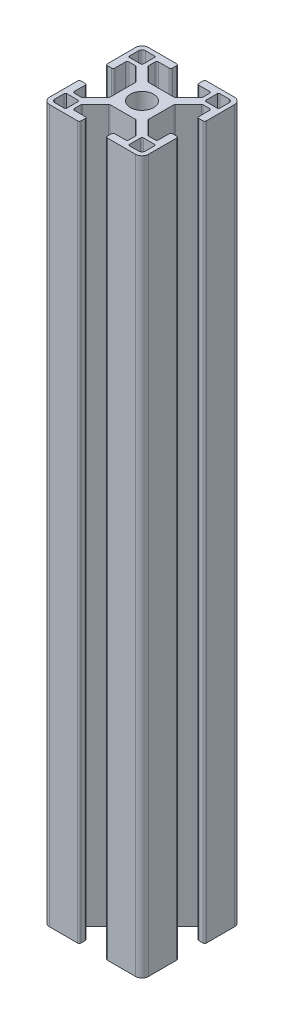
SolidWorks part; units mm, degrees
ref_plane "Front Plane" through (0, 0, 0) normal (0, 0, 1) x (1, 0, 0)
ref_plane "Top Plane" through (0, 0, 0) normal (0, 1, 0) x (1, 0, 0)
ref_plane "Right Plane" through (0, 0, 0) normal (1, 0, 0) x (0, 0, -1)
sketch "Sketch1" plane through (0, 0, 0) normal (0, 1, 0) x (1, 0, 0)
  line L0 (3.9799, -2.4733) -> (3.1981, -1.4942) construction
  line L1 (1.4942, -3.1981) -> (2.4733, -3.9799) construction
  line L2 (-2.4733, -3.9799) -> (-1.4942, -3.1981) construction
  line L3 (-3.1981, -1.4942) -> (-3.9799, -2.4733) construction
  line L4 (-3.9799, 2.4733) -> (-3.1981, 1.4942) construction
  line L5 (-1.4942, 3.1981) -> (-2.4733, 3.9799) construction
  line L6 (2.4733, 3.9799) -> (1.4942, 3.1981) construction
  line L7 (3.1981, 1.4942) -> (3.9799, 2.4733) construction
  line L8 (-12.6999, -13.6999) -> (-9.881, -13.6999)
  line L9 (-13.6999, -9.881) -> (-13.6999, -12.6999)
  line L10 (-9.88, -9.5) -> (-13.3189, -9.5)
  line L11 (-9.5, -13.3189) -> (-9.5, -9.88)
  line L12 (13.6999, -12.6999) -> (13.6999, -9.881)
  line L13 (9.881, -13.6999) -> (12.6999, -13.6999)
  line L14 (9.5, -9.88) -> (9.5, -13.3189)
  line L15 (13.3189, -9.5) -> (9.88, -9.5)
  line L16 (9.88, 9.5) -> (13.3189, 9.5)
  line L17 (9.5, 13.3189) -> (9.5, 9.88)
  line L18 (12.6999, 13.6999) -> (9.881, 13.6999)
  line L19 (13.6999, 9.881) -> (13.6999, 12.6999)
  line L20 (-13.6999, 12.6999) -> (-13.6999, 9.881)
  line L21 (-9.881, 13.6999) -> (-12.6999, 13.6999)
  line L22 (-9.5, 9.88) -> (-9.5, 13.3189)
  line L23 (-13.3189, 9.5) -> (-9.88, 9.5)
  line L24 (14.4999, -4) -> (13.2425, -4)
  line L25 (12.7425, -4.5) -> (12.7425, -7.7325)
  line L26 (12.2428, -8.25) -> (10.2602, -8.25)
  line L27 (9.9066, -8.1035) -> (5.9811, -4.178)
  line L28 (5.8347, -3.8245) -> (5.8347, -1.0125)
  line L29 (5.8347, -1.0125) -> (5.3247, -0.0625) construction
  line L30 (5.3247, -0.0625) -> (5.8347, 0.8875) construction
  line L31 (5.8347, 0.8875) -> (5.8347, 3.8245)
  line L32 (5.9811, 4.178) -> (9.9066, 8.1035)
  line L33 (10.2602, 8.25) -> (12.2428, 8.25)
  line L34 (12.7425, 7.7325) -> (12.7425, 4.5)
  line L35 (13.2425, 4) -> (14.4999, 4)
  line L36 (14.9999, 4.5) -> (14.9999, 12.9999)
  line L37 (12.9999, 14.9999) -> (4.5, 14.9999)
  line L38 (4, 14.4999) -> (4, 13.2425)
  line L39 (4.5, 12.7425) -> (7.7325, 12.7425)
  line L40 (8.25, 12.2428) -> (8.25, 10.2602)
  line L41 (8.1035, 9.9066) -> (4.178, 5.9811)
  line L42 (3.8245, 5.8347) -> (0.95, 5.8347)
  line L43 (0.95, 5.8347) -> (0, 5.3247) construction
  line L44 (0, 5.3247) -> (-0.95, 5.8347) construction
  line L45 (-0.95, 5.8347) -> (-3.8245, 5.8347)
  line L46 (-4.178, 5.9811) -> (-8.1035, 9.9066)
  line L47 (-8.25, 10.2602) -> (-8.25, 12.2428)
  line L48 (-7.7325, 12.7425) -> (-4.5, 12.7425)
  line L49 (-4, 13.2425) -> (-4, 14.4999)
  line L50 (-4.5, 14.9999) -> (-12.9999, 14.9999)
  line L51 (-14.9999, 12.9999) -> (-14.9999, 4.5)
  line L52 (-14.4999, 4) -> (-13.2425, 4)
  line L53 (-12.7425, 4.5) -> (-12.7425, 7.7325)
  line L54 (-12.2428, 8.25) -> (-10.2602, 8.25)
  line L55 (-9.9066, 8.1035) -> (-5.9811, 4.178)
  line L56 (-5.8347, 3.8245) -> (-5.8347, 0.8875)
  line L57 (-5.8347, 0.8875) -> (-5.3247, -0.0625) construction
  line L58 (-5.3247, -0.0625) -> (-5.8347, -1.0125) construction
  line L59 (-5.8347, -1.0125) -> (-5.8347, -3.8245)
  line L60 (-5.9811, -4.178) -> (-9.9066, -8.1035)
  line L61 (-10.2602, -8.25) -> (-12.2428, -8.25)
  line L62 (-12.7425, -7.7325) -> (-12.7425, -4.5)
  line L63 (-13.2425, -4) -> (-14.4999, -4)
  line L64 (-14.9999, -4.5) -> (-14.9999, -12.9999)
  line L65 (-12.9999, -14.9999) -> (-4.5, -14.9999)
  line L66 (-4, -14.4999) -> (-4, -13.2425)
  line L67 (-4.5, -12.7425) -> (-7.7325, -12.7425)
  line L68 (-8.25, -12.2428) -> (-8.25, -10.2602)
  line L69 (-8.1035, -9.9066) -> (-4.178, -5.9811)
  line L70 (-3.8245, -5.8347) -> (-0.95, -5.8347)
  line L71 (-0.95, -5.8347) -> (0, -5.3247) construction
  line L72 (0, -5.3247) -> (0.95, -5.8347) construction
  line L73 (0.95, -5.8347) -> (3.8245, -5.8347)
  line L74 (4.178, -5.9811) -> (8.1035, -9.9066)
  line L75 (8.25, -10.2602) -> (8.25, -12.2428)
  line L76 (7.7325, -12.7425) -> (4.5, -12.7425)
  line L77 (4, -13.2425) -> (4, -14.4999)
  line L78 (4.5, -14.9999) -> (12.9999, -14.9999)
  line L79 (14.9999, -12.9999) -> (14.9999, -4.5)
  line L80 (-5.8347, -1.0125) -> (-5.8347, 0.8875)
  line L81 (-0.95, 5.8347) -> (0.95, 5.8347)
  line L82 (5.8347, 0.8875) -> (5.8347, -1.0125)
  line L83 (-0.95, -5.8347) -> (0.95, -5.8347)
  arc A0 (2.4733, -3.9799) -> (3.9799, -2.4733) centre (3.1422, -3.1422) ccw construction
  arc A1 (-1.4942, -3.1981) -> (1.4942, -3.1981) centre (0, 0) ccw construction
  arc A2 (-3.9799, -2.4733) -> (-2.4733, -3.9799) centre (-3.1422, -3.1422) ccw construction
  arc A3 (-3.1981, 1.4942) -> (-3.1981, -1.4942) centre (0, 0) ccw construction
  arc A4 (-2.4733, 3.9799) -> (-3.9799, 2.4733) centre (-3.1422, 3.1422) ccw construction
  arc A5 (1.4942, 3.1981) -> (-1.4942, 3.1981) centre (0, 0) ccw construction
  arc A6 (3.9799, 2.4733) -> (2.4733, 3.9799) centre (3.1422, 3.1422) ccw construction
  arc A7 (3.1981, -1.4942) -> (3.1981, 1.4942) centre (0, 0) ccw construction
  arc A8 (-13.6999, -12.6999) -> (-12.6999, -13.6999) centre (-12.6999, -12.6999) ccw
  arc A9 (-13.3189, -9.5) -> (-13.6999, -9.881) centre (-13.3189, -9.881) ccw
  arc A10 (-9.5, -9.88) -> (-9.88, -9.5) centre (-9.88, -9.88) ccw
  arc A11 (-9.881, -13.6999) -> (-9.5, -13.3189) centre (-9.881, -13.3189) ccw
  arc A12 (12.6999, -13.6999) -> (13.6999, -12.6999) centre (12.6999, -12.6999) ccw
  arc A13 (9.5, -13.3189) -> (9.881, -13.6999) centre (9.881, -13.3189) ccw
  arc A14 (9.88, -9.5) -> (9.5, -9.88) centre (9.88, -9.88) ccw
  arc A15 (13.6999, -9.881) -> (13.3189, -9.5) centre (13.3189, -9.881) ccw
  arc A16 (9.5, 9.88) -> (9.88, 9.5) centre (9.88, 9.88) ccw
  arc A17 (9.881, 13.6999) -> (9.5, 13.3189) centre (9.881, 13.3189) ccw
  arc A18 (13.6999, 12.6999) -> (12.6999, 13.6999) centre (12.6999, 12.6999) ccw
  arc A19 (13.3189, 9.5) -> (13.6999, 9.881) centre (13.3189, 9.881) ccw
  arc A20 (14.9999, -4.5) -> (14.4999, -4) centre (14.4999, -4.5) ccw
  arc A21 (13.2425, -4) -> (12.7425, -4.5) centre (13.2425, -4.5) ccw
  arc A22 (12.2428, -8.25) -> (12.7425, -7.7325) centre (12.2428, -7.75) ccw
  arc A23 (9.9066, -8.1035) -> (10.2602, -8.25) centre (10.2602, -7.75) ccw
  arc A24 (5.8347, -3.8245) -> (5.9811, -4.178) centre (6.3347, -3.8245) ccw
  arc A25 (5.9811, 4.178) -> (5.8347, 3.8245) centre (6.3347, 3.8245) ccw
  arc A26 (10.2602, 8.25) -> (9.9066, 8.1035) centre (10.2602, 7.75) ccw
  arc A27 (12.7425, 7.7325) -> (12.2428, 8.25) centre (12.2428, 7.75) ccw
  arc A28 (12.7425, 4.5) -> (13.2425, 4) centre (13.2425, 4.5) ccw
  arc A29 (14.4999, 4) -> (14.9999, 4.5) centre (14.4999, 4.5) ccw
  arc A30 (14.9999, 12.9999) -> (12.9999, 14.9999) centre (12.9999, 12.9999) ccw
  arc A31 (4.5, 14.9999) -> (4, 14.4999) centre (4.5, 14.4999) ccw
  arc A32 (4, 13.2425) -> (4.5, 12.7425) centre (4.5, 13.2425) ccw
  arc A33 (8.25, 12.2428) -> (7.7325, 12.7425) centre (7.75, 12.2428) ccw
  arc A34 (8.1035, 9.9066) -> (8.25, 10.2602) centre (7.75, 10.2602) ccw
  arc A35 (3.8245, 5.8347) -> (4.178, 5.9811) centre (3.8245, 6.3347) ccw
  arc A36 (-4.178, 5.9811) -> (-3.8245, 5.8347) centre (-3.8245, 6.3347) ccw
  arc A37 (-8.25, 10.2602) -> (-8.1035, 9.9066) centre (-7.75, 10.2602) ccw
  arc A38 (-7.7325, 12.7425) -> (-8.25, 12.2428) centre (-7.75, 12.2428) ccw
  arc A39 (-4.5, 12.7425) -> (-4, 13.2425) centre (-4.5, 13.2425) ccw
  arc A40 (-4, 14.4999) -> (-4.5, 14.9999) centre (-4.5, 14.4999) ccw
  arc A41 (-12.9999, 14.9999) -> (-14.9999, 12.9999) centre (-12.9999, 12.9999) ccw
  arc A42 (-14.9999, 4.5) -> (-14.4999, 4) centre (-14.4999, 4.5) ccw
  arc A43 (-13.2425, 4) -> (-12.7425, 4.5) centre (-13.2425, 4.5) ccw
  arc A44 (-12.2428, 8.25) -> (-12.7425, 7.7325) centre (-12.2428, 7.75) ccw
  arc A45 (-9.9066, 8.1035) -> (-10.2602, 8.25) centre (-10.2602, 7.75) ccw
  arc A46 (-5.8347, 3.8245) -> (-5.9811, 4.178) centre (-6.3347, 3.8245) ccw
  arc A47 (-5.9811, -4.178) -> (-5.8347, -3.8245) centre (-6.3347, -3.8245) ccw
  arc A48 (-10.2602, -8.25) -> (-9.9066, -8.1035) centre (-10.2602, -7.75) ccw
  arc A49 (-12.7425, -7.7325) -> (-12.2428, -8.25) centre (-12.2428, -7.75) ccw
  arc A50 (-12.7425, -4.5) -> (-13.2425, -4) centre (-13.2425, -4.5) ccw
  arc A51 (-14.4999, -4) -> (-14.9999, -4.5) centre (-14.4999, -4.5) ccw
  arc A52 (-14.9999, -12.9999) -> (-12.9999, -14.9999) centre (-12.9999, -12.9999) ccw
  arc A53 (-4.5, -14.9999) -> (-4, -14.4999) centre (-4.5, -14.4999) ccw
  arc A54 (-4, -13.2425) -> (-4.5, -12.7425) centre (-4.5, -13.2425) ccw
  arc A55 (-8.25, -12.2428) -> (-7.7325, -12.7425) centre (-7.75, -12.2428) ccw
  arc A56 (-8.1035, -9.9066) -> (-8.25, -10.2602) centre (-7.75, -10.2602) ccw
  arc A57 (-3.8245, -5.8347) -> (-4.178, -5.9811) centre (-3.8245, -6.3347) ccw
  arc A58 (4.178, -5.9811) -> (3.8245, -5.8347) centre (3.8245, -6.3347) ccw
  arc A59 (8.25, -10.2602) -> (8.1035, -9.9066) centre (7.75, -10.2602) ccw
  arc A60 (7.7325, -12.7425) -> (8.25, -12.2428) centre (7.75, -12.2428) ccw
  arc A61 (4.5, -12.7425) -> (4, -13.2425) centre (4.5, -13.2425) ccw
  arc A62 (4, -14.4999) -> (4.5, -14.9999) centre (4.5, -14.4999) ccw
  arc A63 (12.9999, -14.9999) -> (14.9999, -12.9999) centre (12.9999, -12.9999) ccw
  arc A64 (-12.6999, 13.6999) -> (-13.6999, 12.6999) centre (-12.6999, 12.6999) ccw
  arc A65 (-9.5, 13.3189) -> (-9.881, 13.6999) centre (-9.881, 13.3189) ccw
  arc A66 (-9.88, 9.5) -> (-9.5, 9.88) centre (-9.88, 9.88) ccw
  arc A67 (-13.6999, 9.881) -> (-13.3189, 9.5) centre (-13.3189, 9.881) ccw
  circle A68 centre (0, 0) radius 3.53
extrude "Boss-Extrude1" add sketch "Sketch1" along normal mid plane 215.9
